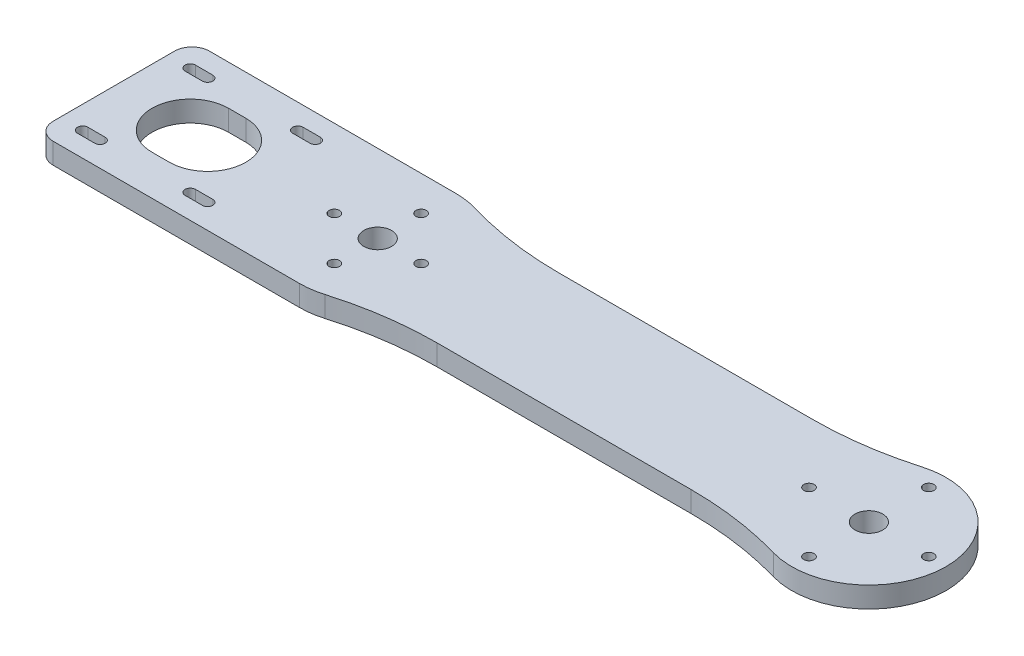
SolidWorks part; units mm, degrees
material "Pine"
ref_plane "Front Plane" through (0, 0, 0) normal (0, 0, 1) x (1, 0, 0)
ref_plane "Top Plane" through (0, 0, 0) normal (0, 1, 0) x (1, 0, 0)
ref_plane "Right Plane" through (0, 0, 0) normal (1, 0, 0) x (0, 0, -1)
sketch "Sketch1" plane through (0, 0, 0) normal (0, 1, 0) x (1, 0, 0)
  line L0 (0, 0) -> (141.5, 0) construction
  line L2 (0, 17.5) -> (141.5, 17.5)
  line L3 (0, -17.5) -> (141.5, -17.5)
  arc A0 (0, 17.5) -> (0, -17.5) centre (0, 0) ccw
  arc A1 (141.5, -17.5) -> (141.5, 17.5) centre (141.5, 0) ccw
  circle A2 centre (141.5, 0) radius 4
  circle A3 centre (0, 0) radius 4
  circle A4 centre (141.5, 0) radius 22.25
  circle A5 centre (0, 0) radius 20
  circle A6 centre (141.5, 0) radius 17.25
  point P5 (70.75, 0)
  dimension "D2" = 17.5
  dimension "D3" = 8
  dimension "D4" = 8
  dimension "D5" = 5
  dimension "D6" = 40
  dimension "D7" = 34.5
  dimension "D1" = 141.5
extrude "Boss-Extrude1" add sketch "Sketch1" along normal blind 6
sketch "Sketch2" plane through (0, 6, 0) normal (0, 1, 0) x (1, 0, 0)
  line L1 (0, 0) -> (-63.5, 0) construction
  line L2 (0, -22.5) -> (-63.5, -22.5)
  line L3 (0, 22.5) -> (-63.5, 22.5)
  line L4 (-69.5, 0) -> (-64.5, 0)
  line L5 (-64.5, 0) -> (-64.5, 15.5)
  line L6 (-64.5, 15.5) -> (-69.5, 15.5) construction
  line L7 (-33.5, 15.5) -> (-38.5, 15.5) construction
  line L8 (-64.5, 14) -> (-69.5, 14)
  line L9 (-64.5, 17) -> (-69.5, 17)
  line L10 (-63.5, 22.5) -> (-76, 22.5)
  line L11 (-63.5, 22.5) -> (-63.5, -22.5)
  line L12 (-63.5, -22.5) -> (-76, -22.5)
  line L13 (-76, 22.5) -> (-76, -22.5)
  line L14 (-33.5, 14) -> (-38.5, 14)
  line L15 (-33.5, 17) -> (-38.5, 17)
  line L16 (-33.5, -15.5) -> (-38.5, -15.5) construction
  line L17 (-33.5, -17) -> (-38.5, -17)
  line L18 (-33.5, -14) -> (-38.5, -14)
  line L19 (-64.5, -15.5) -> (-69.5, -15.5) construction
  line L20 (-64.5, -17) -> (-69.5, -17)
  line L21 (-64.5, -14) -> (-69.5, -14)
  line L22 (-67, 15.5) -> (-36, -15.5)
  line L23 (-54, 0) -> (-49, 0) construction
  line L25 (-54, 11) -> (-49, 11)
  line L26 (-54, -11) -> (-49, -11)
  arc A0 (0, -22.5) -> (0, 22.5) centre (0, 0) ccw
  arc A1 (-63.5, 22.5) -> (-63.5, -22.5) centre (-63.5, 0) ccw
  circle A2 centre (0, 0) radius 4
  arc A3 (-64.5, 14) -> (-64.5, 17) centre (-64.5, 15.5) ccw
  arc A4 (-69.5, 17) -> (-69.5, 14) centre (-69.5, 15.5) ccw
  arc A5 (-33.5, 14) -> (-33.5, 17) centre (-33.5, 15.5) ccw
  arc A6 (-38.5, 17) -> (-38.5, 14) centre (-38.5, 15.5) ccw
  arc A7 (-33.5, -17) -> (-33.5, -14) centre (-33.5, -15.5) ccw
  arc A8 (-38.5, -14) -> (-38.5, -17) centre (-38.5, -15.5) ccw
  arc A9 (-64.5, -17) -> (-64.5, -14) centre (-64.5, -15.5) ccw
  arc A10 (-69.5, -14) -> (-69.5, -17) centre (-69.5, -15.5) ccw
  arc A11 (-54, 11) -> (-54, -11) centre (-54, 0) ccw
  arc A12 (-49, -11) -> (-49, 11) centre (-49, 0) ccw
  point P3 (-31.75, 0)
  point P16 (-67, 15.5)
  point P28 (-36, 15.5)
  point P35 (-36, -15.5)
  point P42 (-67, -15.5)
  point P50 (-51.5, 0)
  dimension "D2" = 22.5
  dimension "D3" = 51.5
  dimension "D1" = 63.5
  dimension "D4" = 12.5
  dimension "D5" = 2
  dimension "D7" = 0
  dimension "D6" = 2
extrude "Boss-Extrude2" add sketch "Sketch2" against normal blind 6
fillet "Fillet1" radius 5 2 edges at (-76, 3, 22.5) (-76, 3, -22.5)
sketch "Sketch3" plane through (0, 6, 0) normal (0, 1, 0) x (1, 0, 0)
  circle A0 centre (0, 0) radius 12.5
  circle A1 centre (0, 12.5) radius 1.5
  circle A2 centre (12.5, 0) radius 1.5
  circle A3 centre (0, -12.5) radius 1.5
  circle A4 centre (-12.5, 0) radius 1.5
  dimension "D1" = 25
  dimension "D2" = 3
  dimension "D3" = 4
extrude "Cut-Extrude1" cut sketch "Sketch3" against normal blind 19 contours A1 | A4 | A2 | A3
sketch "Sketch4" plane through (0, 6, 0) normal (0, 1, 0) x (1, 0, 0)
  circle A0 centre (141.5, 0) radius 17.25
  circle A1 centre (141.5, 0) radius 227.9116
  circle A2 centre (141.5, 0) radius 17.25
  circle A3 centre (158.75, 0) radius 1.5
  circle A4 centre (141.5, -17.25) radius 1.5
  circle A5 centre (124.25, 0) radius 1.5
  circle A6 centre (141.5, 17.25) radius 1.5
  circle A7 centre (141.5, 0) radius 17.25
  circle A8 centre (141.5, 0) radius 17.25
  dimension "D1" = 34.5
  dimension "D2" = 4
  dimension "D3" = 3
extrude "Cut-Extrude2" cut sketch "Sketch4" against normal blind 19 contours A3 | A6 | A5 | A4
fillet "Fillet2" radius 100 4 edges at (127.7591, 3, -17.5) (127.7591, 3, 17.5) (14.1421, 3, -17.5) (14.1421, 3, 17.5)
